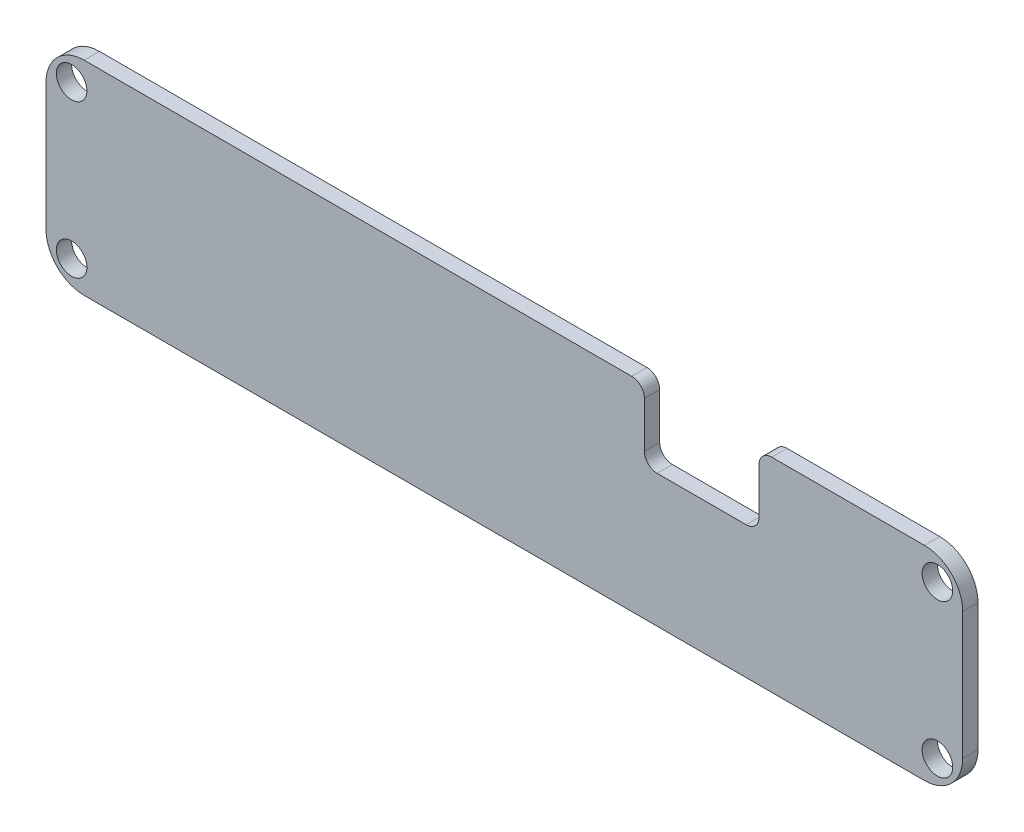
SolidWorks part; units mm, degrees
ref_plane "前视基准面" through (0, 0, 0) normal (0, 0, 1) x (1, 0, 0)
ref_plane "上视基准面" through (0, 0, 0) normal (0, 1, 0) x (1, 0, 0)
ref_plane "右视基准面" through (0, 0, 0) normal (1, 0, 0) x (0, 0, -1)
other "Configuration Table"
sketch "草图1" plane through (0, 0, 0) normal (0, 0, 1) x (1, 0, 0)
  line L1 (0, 0) -> (72, 0)
  line L2 (0, 0) -> (0, 16)
  line L3 (0, 16) -> (72, 16)
  line L4 (72, 0) -> (72, 16)
  dimension "D1" = 72
  dimension "D2" = 16
extrude "凸台-拉伸1" add sketch "草图1" along normal blind 1.2
fillet "圆角1" radius 3 4 edges at (0, 0, 0.6) (0, 16, 0.6) (72, 0, 0.6) (72, 16, 0.6)
sketch "草图3" plane through (0, 0, 0) normal (0, 0, -1) x (-1, 0, 0)
  circle A0 centre (-70.0129, 14.013) radius 1.2
  circle A1 centre (-70.0127, 2.0127) radius 1.2
  circle A2 centre (-2.0119, 14.012) radius 1.2
  circle A3 centre (-2.0125, 2.013) radius 1.2
  dimension "D1" = 2.4
extrude "切除-拉伸1" cut sketch "草图3" against normal up to next
sketch "草图4" plane through (0, 0, 0) normal (0, 0, -1) x (-1, 0, 0)
  line L1 (-56, 16.4) -> (-47, 16.4)
  line L2 (-56, 16.4) -> (-56, 10.4)
  line L3 (-56, 10.4) -> (-47, 10.4)
  line L4 (-47, 16.4) -> (-47, 10.4)
  point P4 (-56, 16.4)
  dimension "D1" = 6
  dimension "D2" = 9
extrude "切除-拉伸2" cut sketch "草图4" against normal up to next
fillet "圆角2" radius 1 4 edges at (47, 10.4, 0.6) (56, 10.4, 0.6) (47, 16, 0.6) (56, 16, 0.6)
